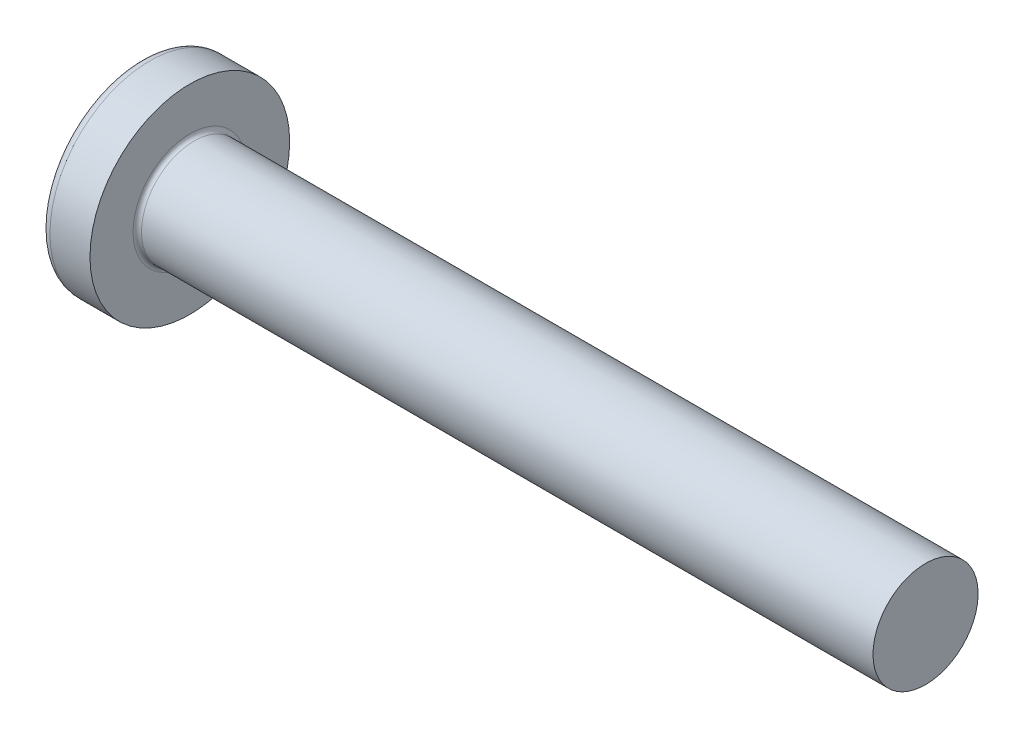
SolidWorks part; units mm, degrees
ref_plane "Plane1" through (0, 0, 0) normal (0, 0, 1) x (1, 0, 0)
ref_plane "Plane2" through (0, 0, 0) normal (0, 1, 0) x (1, 0, 0)
ref_plane "Plane3" through (0, 0, 0) normal (1, 0, 0) x (0, 0, -1)
sketch "BodySke" plane through (0, 0, 0) normal (0, 0, 1) x (1, 0, 0)
  line L0 (3.7, 2.5) -> (3.7, 4.75)
  line L1 (4.1, 6.35) -> (4.1, -3.175) construction
  line L2 (-25.4, 0) -> (127, 0) construction
  line L3 (38.7, 0) -> (0, 0)
  line L4 (3.7, 2.5) -> (38.7, 2.5)
  line L5 (38.7, 2.5) -> (38.7, 0)
  line L6 (1.7942, 4.75) -> (3.7, 4.75)
  line L8 (3.7, 6.35) -> (3.7, -3.175) construction
  arc A0 (1.4243, 4.5563) -> (0, 0) centre (8, 0) ccw
  arc A2 (1.4243, 4.5563) -> (1.7942, 4.75) centre (1.7942, 4.3) cw
  dimension "Head_fillet_rad" = 0.45
  dimension "Head_crown_rad" = 8
  dimension "Head_ht" = 3.7
  dimension "Diameter" = 5
  dimension "Length" = 35
  dimension "Head_dia" = 9.5
  dimension "Advance" = 0.8
  dimension "Thread_nom" = 35
revolve "Base-Revolve" add sketch "BodySke"
cosmetic thread "ThreadCosmetic" [suppressed]
fillet "Fillet1" radius 0.2 1 edges at (3.7, 0, 2.5)
sketch "Sketch3" plane through (0, 0, 0) normal (1, 0, 0) x (0, 0, -1)
  line L0 (0.515, -2.35) -> (-0.515, -2.35)
  line L1 (0.515, -2.35) -> (0.515, 2.35)
  line L2 (-0.515, 2.35) -> (0.515, 2.35)
  line L3 (-0.515, 2.35) -> (-0.515, -2.35)
  dimension "D1" = 2.35
  dimension "Cross_dia" = 4.7
  dimension "D2" = 0.515
  dimension "Cross_width" = 1.03
ref_plane "Plane4" through (2.74, 0, 0) normal (1, 0, 0) x (0, 0, -1)
sketch "Sketch4" plane through (2.74, 0, 0) normal (1, 0, 0) x (0, 0, -1)
  line L0 (0.515, -0.9839) -> (-0.515, -0.9839)
  line L1 (0.515, -0.9839) -> (0.515, 0.9839)
  line L2 (-0.515, 0.9839) -> (0.515, 0.9839)
  line L3 (-0.515, 0.9839) -> (-0.515, -0.9839)
  dimension "D1" = 1.03
  dimension "D2" = 1.9678
  dimension "D3" = 0.515
  dimension "D4" = 0.9839
loft "Recess" cut profiles "Sketch3", "Sketch4"
pattern_circular "RecPat" count 2 every 90 about axis through (0, 0, 0) along (1, 0, 0) of "Recess"
sketch "RecCorSke" plane through (0, 0, 0) normal (0, 0, 1) x (1, 0, 0)
  line L0 (-3.175, 0) -> (15.875, 0) construction
  line L1 (-25.4, 0) -> (127, 0) construction
  line L2 (0, 0) -> (0, 1.0426)
  line L3 (0, 1.0426) -> (2.74, 0.851)
  line L4 (2.74, 0.851) -> (3.0165, 0)
  line L5 (3.0165, 0) -> (0, 0)
  dimension "Diameter" = 1.702
  dimension "Depth" = 2.74
  dimension "Draft_angle" = 4
  dimension "Bottom_angle" = 18
revolve "RecessCore" cut sketch "RecCorSke" angle 360 about L0
sketch "ThdSchSke" plane through (0, 0, 0) normal (0, 0, 1) x (1, 0, 0)
  line L0 (5.3, -2.055) -> (4.9884, -2.5)
  line L1 (5.3, -2.055) -> (5.6116, -2.5)
  line L2 (5.6116, -2.5) -> (5.6116, -3.125)
  line L3 (-3.175, 0) -> (5.1513, 0) construction
  line L5 (5.6116, -3.125) -> (4.9884, -3.125)
  line L6 (4.9884, -3.125) -> (4.9884, -2.5)
  dimension "Thread_minor" = 4.11
  dimension "Diameter" = 5
  dimension "Start" = 5.3
  dimension "SideAngle" = 55
  dimension "VeeAngle" = 70
  dimension "Overcut" = 6.25
revolve "ThreadSchematic" [suppressed] cut sketch "ThdSchSke" angle 360 about L3
pattern_linear "ThdSchPat" [suppressed]
equation "\"D1@Sketch3\" = \"Cross_dia@Sketch3\" / 2"
equation "\"D2@Sketch3\" = \"Cross_width@Sketch3\" / 2"
equation "\"Depth@RecCorSke\" = \"Cross_depth@Plane4\""
equation "\"D1@Sketch4\" = \"Cross_width@Sketch3\""
equation "\"D2@Sketch4\" = \"Cross_dia@Sketch3\" - 2.0 * \"Cross_depth@Plane4\" * tan(26.5  * 0.017453292)"
equation "\"D3@Sketch4\" = \"D1@Sketch4\" / 2"
equation "\"D4@Sketch4\" = \"D2@Sketch4\" / 2"
equation "\"Thread_length@ThreadCosmetic\" = ((sgn( (\"Length@BodySke\" - \"Advance@BodySke\" * 2.0 ) - \"Thread_nom@BodySke\" )-1)*( (\"Length@BodySke\" - \"Advance@BodySke\" * 2.0 ) - \"Thread_nom@BodySke\" ))/-2+ \"Thread_nom@BodySke\""
equation "\"Thread_minor@ThdSchSke\" = \"Thread_minor@ThreadCosmetic\""
equation "\"Diameter@ThdSchSke\" = \"Diameter@BodySke\""
equation "\"Overcut@ThdSchSke\" = \"Diameter@BodySke\" * 1.25"
equation "\"Start@ThdSchSke\" = \"Head_ht@BodySke\" + \"Length@BodySke\" - \"Thread_length@ThreadCosmetic\"  '---Non-countersunk---"
equation "\"Num_threads@ThdSchPat\" = int( \"Thread_length@ThreadCosmetic\" / \"Advance@BodySke\" + 0.999 )  + 1"
equation "\"Advance@ThdSchPat\" = \"Thread_length@ThreadCosmetic\" /  (\"Num_threads@ThdSchPat\" - 1) 'relax it"
